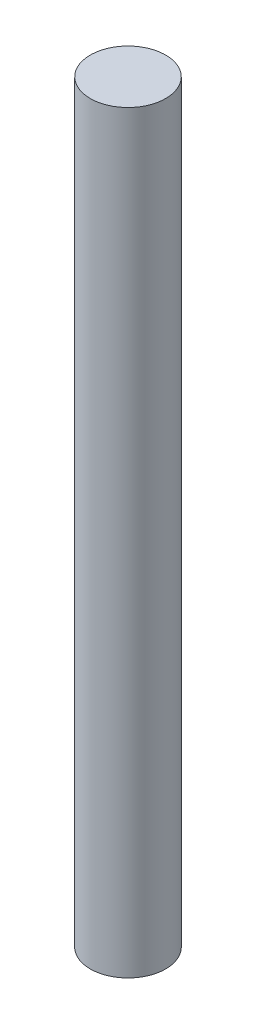
SolidWorks part; units mm, degrees
ref_plane "前视基准面" through (0, 0, 0) normal (0, 0, 1) x (1, 0, 0)
ref_plane "上视基准面" through (0, 0, 0) normal (0, 1, 0) x (1, 0, 0)
ref_plane "右视基准面" through (0, 0, 0) normal (1, 0, 0) x (0, 0, -1)
sketch "草图2" plane through (0, 0, 0) normal (1, 0, 0) x (0, 0, -1)
  line L1 (-2.5, 50) -> (2.5, 50)
  line L2 (-2.5, 50) -> (-2.5, -50)
  line L3 (-2.5, -50) -> (2.5, -50)
  line L4 (2.5, 50) -> (2.5, -50)
  line L5 (-2.5, 50) -> (2.5, -50) construction
  line L6 (-2.5, -50) -> (2.5, 50) construction
  point P0 (0, 0)
  dimension "D1" = 5
  dimension "D2" = 100
revolve "旋转2" add sketch "草图2" angle 360 about L2
